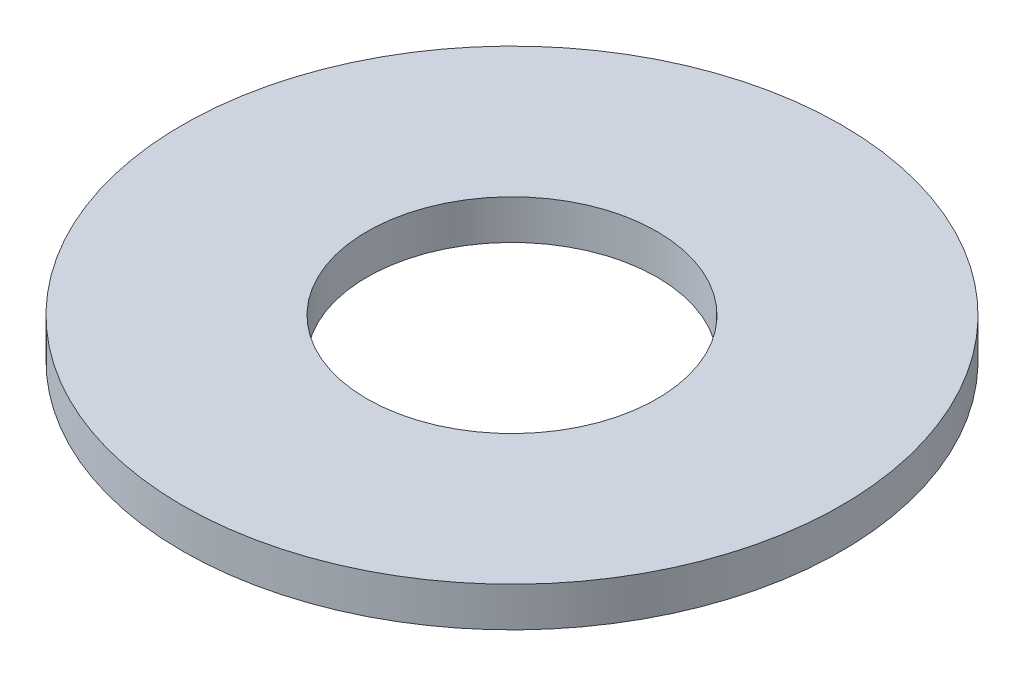
SolidWorks part; units mm, degrees
ref_plane "Спереди" through (0, 0, 0) normal (0, 0, 1) x (1, 0, 0)
ref_plane "Сверху" through (0, 0, 0) normal (0, 1, 0) x (1, 0, 0)
ref_plane "Справа" through (0, 0, 0) normal (1, 0, 0) x (0, 0, -1)
sketch "Эскиз1" plane through (0, 0, 0) normal (0, 1, 0) x (1, 0, 0)
  circle A0 centre (0, 0) radius 2.5
  dimension "D1" = 5
extrude "Вытянуть1" add sketch "Эскиз1" along normal blind 0.3
sketch "Эскиз2" plane through (0, 0.3, 0) normal (0, 1, 0) x (-1, 0, 0)
  circle A0 centre (0, 0) radius 1.1
  dimension "D1" = 2.2
extrude "Вырез-Вытянуть1" cut sketch "Эскиз2" against normal blind 0.8
